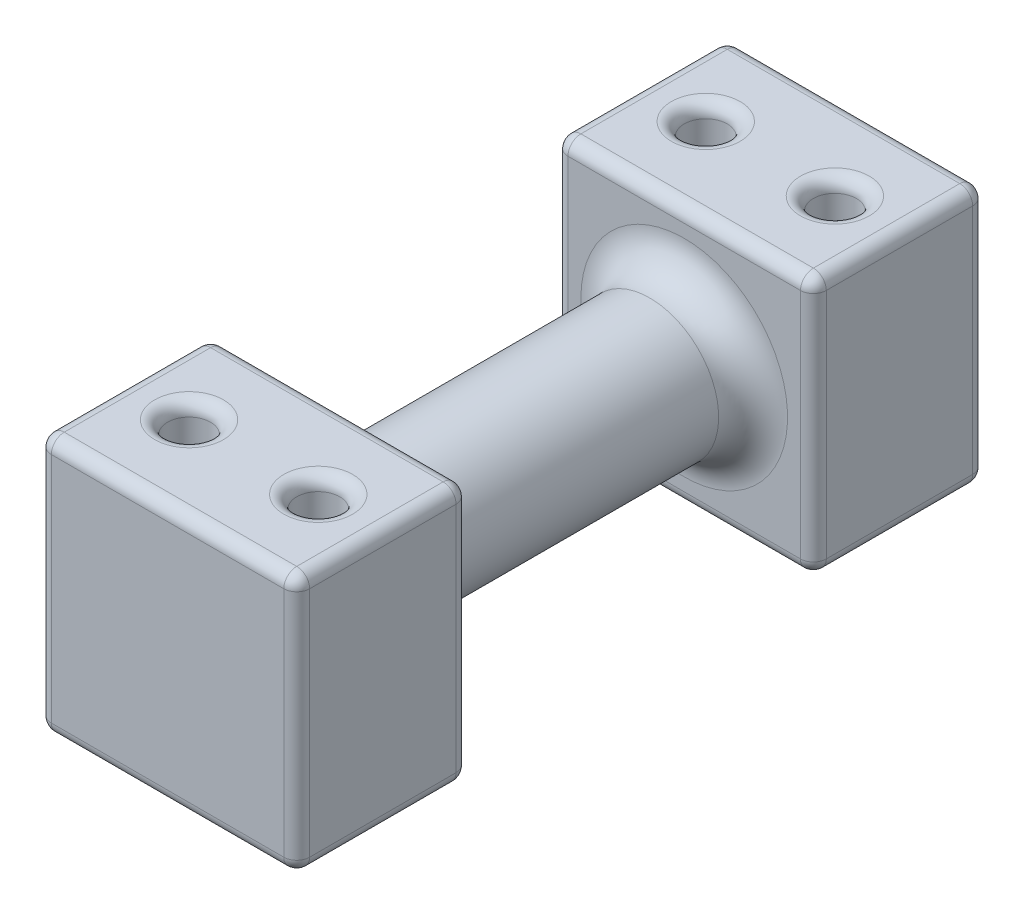
SolidWorks part; units mm, degrees
ref_plane "Alzado" through (0, 0, 0) normal (0, 0, 1) x (1, 0, 0)
ref_plane "Planta" through (0, 0, 0) normal (0, 1, 0) x (1, 0, 0)
ref_plane "Vista lateral" through (0, 0, 0) normal (1, 0, 0) x (0, 0, -1)
sketch "Croquis1" plane through (0, 0, 0) normal (0, 0, 1) x (1, 0, 0)
  line L1 (0, 0) -> (15, 0)
  line L2 (0, 0) -> (0, 15)
  line L3 (0, 15) -> (15, 15)
  line L4 (15, 0) -> (15, 15)
  dimension "D1" = 15
  dimension "D2" = 15
extrude "Saliente-Extruir1" add sketch "Croquis1" along normal blind 10
sketch "Croquis2" plane through (0, 0, 10) normal (0, 0, 1) x (1, 0, 0)
  line L0 (0, 7.5) -> (15, 7.5) construction
  line L1 (0, 15) -> (0, 0) construction
  line L2 (15, 0) -> (15, 15) construction
  circle A0 centre (7.5, 7.5) radius 4
  point P10 (7.5, 7.5)
  dimension "D1" = 8
extrude "Saliente-Extruir2" add sketch "Croquis2" along normal blind 10
sketch "Croquis3" plane through (0, 15, 0) normal (0, 1, 0) x (1, 0, 0)
  line L0 (7.5, 0) -> (7.5, -10) construction
  line L1 (15, 0) -> (0, 0) construction
  line L2 (3.5, -10) -> (11.5, -10) construction
  line L3 (7.5, -5) -> (0, -5) construction
  line L4 (0, -10) -> (0, 0) construction
  line L5 (7.5, -5) -> (15, -5) construction
  line L6 (15, -10) -> (15, 0) construction
  circle A0 centre (3.75, -5) radius 1.25
  circle A1 centre (11.25, -5) radius 1.25
  dimension "D1" = 2.5
extrude "Cortar-Extruir1" cut sketch "Croquis3" against normal through all
mirror "Simetría1" about plane through (7.5, 7.5, 20) normal (0, 0, 1) of bodies 104 102
fillet "Redondeo1" radius 0.75 32 edges at (15, 7.5, 40) (15, 7.5, 30) (15, 0, 35) (7.5, 0, 30) (7.5, 0, 40) (11.25, 0, 33.75) (3.75, 0, 33.75) (0, 0, 35) (0, 7.5, 30) (0, 7.5, 40) (7.5, 0, 10) (11.25, 0, 6.25) (3.75, 0, 6.25) (0, 7.5, 10) (0, 0, 5) (7.5, 0, 0) (0, 7.5, 0) (15, 0, 5) (15, 7.5, 10) (15, 7.5, 0) (15, 15, 5) (7.5, 15, 10) (0, 15, 5) (7.5, 15, 0) (11.25, 15, 6.25) (3.75, 15, 6.25) (0, 15, 35) (7.5, 15, 30) (15, 15, 35) (7.5, 15, 40) (11.25, 15, 33.75) (3.75, 15, 33.75)
fillet "Redondeo2" radius 2 2 edges at (11.5, 7.5, 30) (11.5, 7.5, 10)
